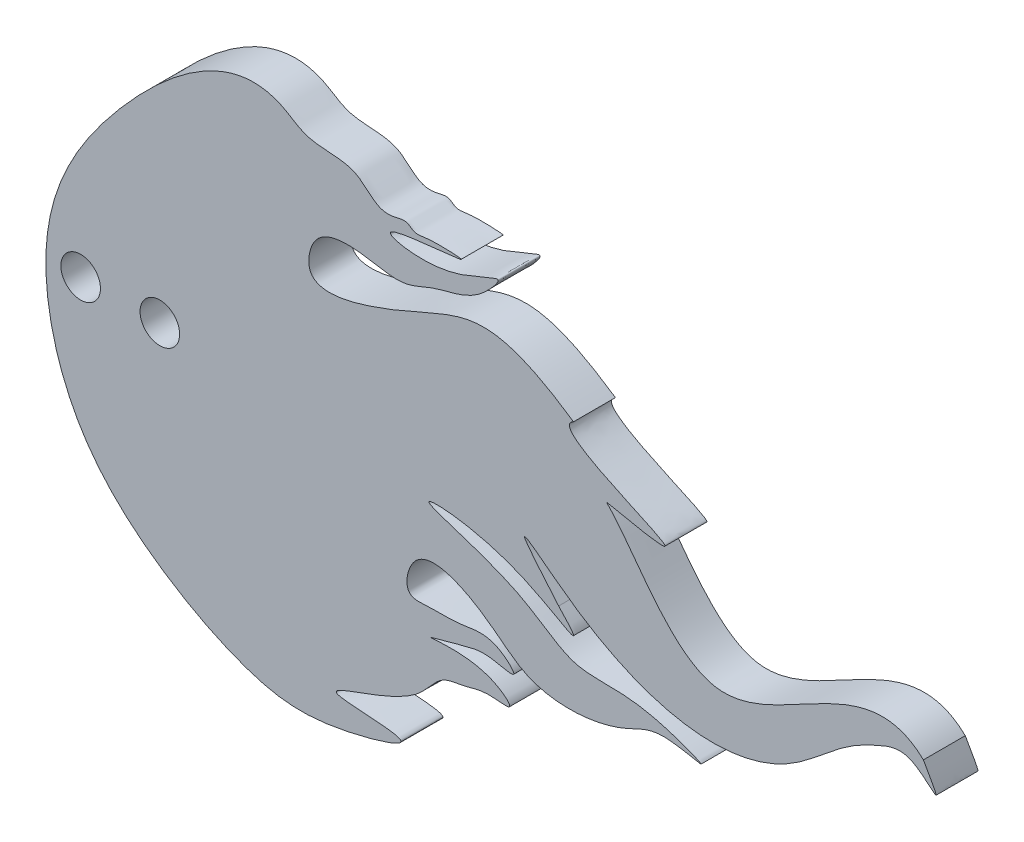
SolidWorks part; units mm, degrees
ref_plane "前视基准面" through (0, 0, 0) normal (0, 0, 1) x (1, 0, 0)
ref_plane "上视基准面" through (0, 0, 0) normal (0, 1, 0) x (1, 0, 0)
ref_plane "右视基准面" through (0, 0, 0) normal (1, 0, 0) x (0, 0, -1)
sketch "Sketch1" plane through (0, 0, 0) normal (0, 0, 1) x (1, 0, 0)
  line L0 (125.0813, 142.4115) -> (125.0813, 99.0768) construction
  line L1 (0, 0) -> (0, 22.8) construction
  line L2 (0, 22.8) -> (26.2914, 22.8) construction
  dimension "D1" = 22.8
sketch "Sketch2" plane through (0, 0, 0) normal (0, 0, 1) x (1, 0, 0)
  line L0 (0, 22.8) -> (26.2914, 22.8) construction
  spline S0 degree 3 poles (41.3549, 31.023) (38.5475, 29.6) (56.1974, 24.3517) (43.8487, 27.0053) knots 0 0 0 0 1 1 1 1
  spline S1 degree 3 poles (43.8487, 27.0053) (46.004, 24.8762) (52.3174, 12.2333) (63.2922, 26.4734) (67.8735, 22.0911) knots 0 0 0 0 0.418791 1 1 1 1
  spline S2 degree 3 poles (67.8735, 22.0911) (69.9523, 18.4637) (67.4332, 22.4941) (64.4287, 21.3719) (61.496, 19.9095) (55.4749, 13.7665) (44.2479, 15.2775) (35.3562, 24.0141) (40.2271, 18.3679) knots 0 0 0 0 0.113497 0.167733 0.228167 0.362892 0.786599 1 1 1 1
  spline S3 degree 3 poles (40.2271, 18.3679) (42.971, 15.4798) (37.2288, 20.1929) (26.6611, 20.8177) (37.1402, 18.3887) (41.4366, 14.3916) (45.6941, 15.6237) (52.9856, 12.729) (47.7063, 14.2404) (44.2412, 11.9898) (38.3125, 11.5138) (34.663, 15.2422) (29.2366, 17.7622) (28.4194, 13.2105) (30.7903, 13.45) (32.9244, 13.3097) (35.1052, 14.0541) (37.5012, 11.7935) (34.6396, 12.6178) (33.2156, 12.1927) (28.4735, 10.9559) (34.1782, 12.1713) (37.1849, 9.5875) (34.5164, 10.0919) (33.301, 9.5034) (30.9822, 9.2696) (29.5744, 5.9489) (19.0096, 3.8689) (31.0703, 3.9966) (22.2737, 1.3804) (17.3162, 1.7535) (9.7047, 5.5967) (2.8571, 11.8467) (-0.0024, 23.76) (5.8912, 34.5286) (16.04, 43.3008) (21.5601, 39.098) (24.7054, 39.874) (26.3919, 37.5724) (27.813, 37.633) (28.7032, 37.9508) (29.2629, 37.3512) (30.087, 37.4928) (31.1121, 37.5732) (35.2318, 37.3959) (23.8401, 36.8364) (31.9137, 35.1994) (36.719, 38.515) (33.7164, 34.9731) (31.2449, 34.8743) (28.3802, 33.3674) (25.4706, 34.1587) (21.6781, 34.2388) (20.7696, 29.4458) (32.2978, 32.3566) (33.972, 36.0531) (41.3549, 31.023) knots 0 0 0 0 0.027351 0.057226 0.087606 0.109238 0.134203 0.151916 0.164943 0.176883 0.209685 0.22636 0.250124 0.25903 0.264876 0.275127 0.288486 0.294765 0.30129 0.311926 0.3222 0.34283 0.349609 0.355757 0.365471 0.37036 0.383662 0.412376 0.433049 0.449797 0.482244 0.514623 0.552538 0.601392 0.656705 0.716729 0.724524 0.742273 0.751842 0.756282 0.760054 0.762807 0.76554 0.769993 0.777855 0.800706 0.819907 0.836431 0.844656 0.86197 0.871044 0.884062 0.901213 0.910338 0.93154 1 1 1 1
extrude "Boss-Extrude1" add sketch "Sketch2" along normal blind 3.175
sketch "Sketch3" plane through (0, 0, 3.175) normal (0, 0, 1) x (1, 0, 0)
  line L0 (4, 21.8382) -> (17.9347, 21.8382) construction
  circle A0 centre (4, 21.8382) radius 1.5
  circle A1 centre (10, 21.8382) radius 1.5
  dimension "D1" = 3
  dimension "D3" = 3
  dimension "D2" = 4
  dimension "D4" = 6
extrude "Cut-Extrude1" cut sketch "Sketch3" against normal through all
